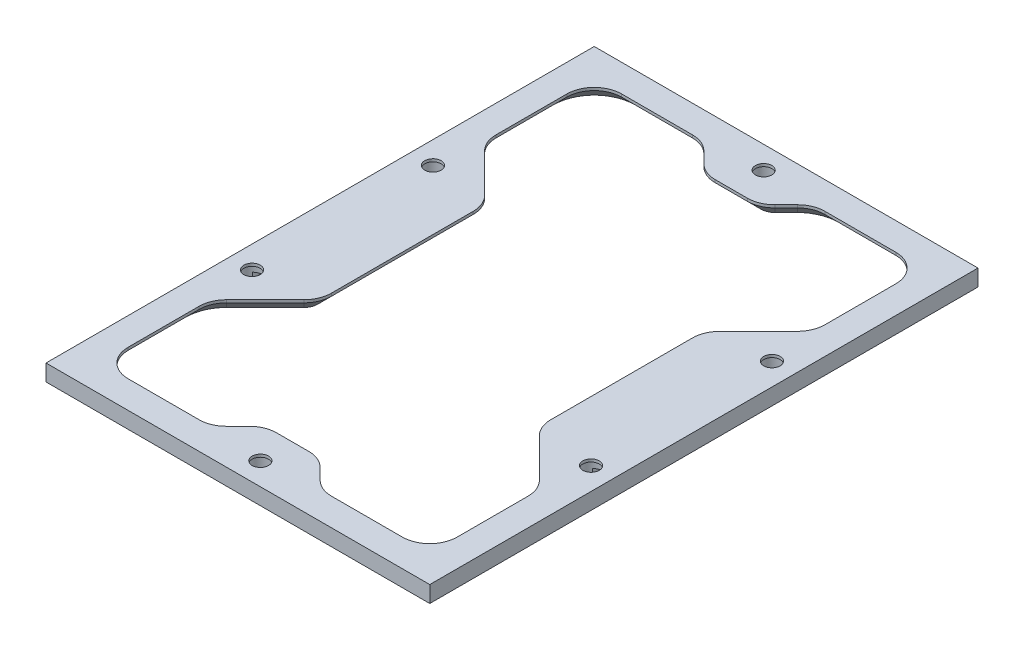
SolidWorks part; units mm, degrees
other "Markup1"
sketch "Sketch5" plane through (140, 0, -160) normal (0.8676, -0.3882, -0.3107) x (0.4165, 0.2261, 0.8806)
ref_plane "Front Plane" through (0, 0, 0) normal (0, 0, 1) x (1, 0, 0)
ref_plane "Top Plane" through (0, 0, 0) normal (0, 1, 0) x (1, 0, 0)
ref_plane "Right Plane" through (0, 0, 0) normal (1, 0, 0) x (0, 0, -1)
sketch "Sketch1" plane through (0, 0, 0) normal (0, 1, 0) x (1, 0, 0)
  line L0 (10, 190) -> (50, 190)
  line L1 (0, 0) -> (140, 0)
  line L2 (0, 0) -> (0, 200)
  line L3 (0, 200) -> (140, 200)
  line L4 (140, 0) -> (140, 200)
  line L5 (50, 190) -> (60, 180)
  line L6 (60, 180) -> (80, 180)
  line L7 (80, 180) -> (90, 190)
  line L8 (90, 190) -> (130, 190)
  line L9 (130, 190) -> (130, 150)
  line L10 (130, 150) -> (110, 130)
  line L11 (110, 130) -> (110, 70)
  line L12 (110, 70) -> (130, 50)
  line L13 (130, 50) -> (130, 10)
  line L14 (130, 10) -> (90, 10)
  line L15 (90, 10) -> (80, 20)
  line L16 (80, 20) -> (60, 20)
  line L17 (60, 20) -> (50, 10)
  line L18 (50, 10) -> (10, 10)
  line L19 (10, 10) -> (10, 50)
  line L20 (10, 50) -> (30, 70)
  line L21 (30, 70) -> (30, 130)
  line L22 (30, 130) -> (10, 150)
  line L23 (10, 150) -> (10, 190)
  dimension "D1" = 200
  dimension "D2" = 140
  dimension "D3" = 10
  dimension "D4" = 10
  dimension "D5" = 10
  dimension "D6" = 10
  dimension "D7" = 10
  dimension "D8" = 10
  dimension "D9" = 30
  dimension "D10" = 30
  dimension "D12" = 10
  dimension "D13" = 40
  dimension "D14" = 10
  dimension "D15" = 40
  dimension "D16" = 40
  dimension "D17" = 40
  dimension "D18" = 40
  dimension "D19" = 20
  dimension "D20" = 135
  dimension "D21" = 135
  dimension "D22" = 135
  dimension "D23" = 135
  dimension "D24" = 60
  dimension "D25" = 60
  dimension "D26" = 135
  dimension "D27" = 135
  dimension "D28" = 40
  dimension "D29" = 40
  dimension "D30" = 135
  dimension "D31" = 135
  dimension "D32" = 40
  dimension "D33" = 20
extrude "Boss-Extrude1" add sketch "Sketch1" along normal blind 6
fillet "Fillet1" radius 10 1 edges at (10, 3, -190)
fillet "Fillet2" radius 10 19 edges at (10, 3, -150) (30, 3, -130) (30, 3, -70) (10, 3, -50) (10, 3, -10) (50, 3, -10) (60, 3, -20) (80, 3, -20) (90, 3, -10) (130, 3, -10) (130, 3, -50) (110, 3, -70) (110, 3, -130) (130, 3, -150) (130, 3, -190) (90, 3, -190) (80, 3, -180) (60, 3, -180) (50, 3, -190)
chamfer "Chamfer4" distance 5 distance2 5 40 edges at (127.0711, 0, -187.0711) (107.0711, 0, -190) (90.3153, 0, -189.2388) (85, 0, -185) (79.6847, 0, -180.7612) (70, 0, -180) (60.3153, 0, -180.7612) (55, 0, -185) (49.6847, 0, -189.2388) (32.9289, 0, -190) (12.9289, 0, -187.0711) (10, 0, -167.0711) (10.7612, 0, -150.3153) (20, 0, -140) (29.2388, 0, -129.6847) (30, 0, -100) (29.2388, 0, -70.3153) (20, 0, -60) (10.7612, 0, -49.6847) (10, 0, -32.9289) (12.9289, 0, -12.9289) (32.9289, 0, -10) (49.6847, 0, -10.7612) (55, 0, -15) (60.3153, 0, -19.2388) (70, 0, -20) (79.6847, 0, -19.2388) (85, 0, -15) (90.3153, 0, -10.7612) (107.0711, 0, -10) (127.0711, 0, -12.9289) (130, 0, -32.9289) (129.2388, 0, -49.6847) (120, 0, -60) (110.7612, 0, -70.3153) (110, 0, -100) (110.7612, 0, -129.6847) (120, 0, -140) (129.2388, 0, -150.3153) (130, 0, -167.0711)
sketch "Sketch6" plane through (0, 0, 0) normal (0, -1, 0) x (1, 0, 0)
  line L0 (70, -200) -> (70, 0) construction
  line L1 (140, -200) -> (0, -200) construction
  line L2 (0, 0) -> (140, 0) construction
  line L3 (121, -125) -> (121, -75) construction
  line L4 (118, -125) -> (118, -75)
  line L5 (124, -125) -> (124, -75)
  line L6 (132, -133.0286) -> (132, -67.0286) construction
  line L7 (129, -133.0286) -> (129, -67.0286)
  line L8 (135, -133.0286) -> (135, -67.0286)
  line L9 (140, 0) -> (140, -200) construction
  line L11 (115, -74.1421) -> (115, -125.8579) construction
  line L12 (115, -100) -> (159.3934, -100) construction
  line L13 (19, -125) -> (19, -75) construction
  line L14 (22, -125) -> (22, -75)
  line L15 (16, -125) -> (16, -75)
  line L16 (8, -133.0286) -> (8, -67.0286) construction
  line L17 (11, -133.0286) -> (11, -67.0286)
  line L18 (5, -133.0286) -> (5, -67.0286)
  arc A0 (118, -125) -> (124, -125) centre (121, -125) ccw
  arc A1 (124, -75) -> (118, -75) centre (121, -75) ccw
  arc A2 (129, -133.0286) -> (135, -133.0286) centre (132, -133.0286) ccw
  arc A3 (135, -67.0286) -> (129, -67.0286) centre (132, -67.0286) ccw
  arc A4 (22, -125) -> (16, -125) centre (19, -125) cw
  arc A5 (16, -75) -> (22, -75) centre (19, -75) cw
  arc A6 (11, -133.0286) -> (5, -133.0286) centre (8, -133.0286) cw
  arc A7 (5, -67.0286) -> (11, -67.0286) centre (8, -67.0286) cw
  point P8 (121, -100)
  point P13 (132, -100.0286)
  point P30 (19, -100)
  point P37 (8, -100.0286)
  dimension "D1" = 3
  dimension "D2" = 3
  dimension "D3" = 5
  dimension "D4" = 5
  dimension "D5" = 0
  dimension "D6" = 33
  dimension "D7" = 25
extrude "Cut-Extrude1" cut sketch "Sketch6" against normal blind 2
sketch "Sketch7" plane through (0, 6, 0) normal (0, 1, 0) x (1, 0, 0)
  line L0 (0, 100) -> (140, 100) construction
  line L1 (0, 200) -> (0, 0) construction
  line L2 (140, 0) -> (140, 200) construction
  line L3 (70, 0) -> (70, 200) construction
  line L4 (0, 0) -> (140, 0) construction
  line L5 (140, 200) -> (0, 200) construction
  line L6 (140, 200) -> (0, 200) construction
  line L7 (0, 200) -> (0, 0) construction
  circle A0 centre (70, 191.8) radius 3
  circle A2 centre (8.1661, 133) radius 3
  circle A3 centre (70, 8.2) radius 3
  circle A4 centre (8.1661, 67) radius 3
  circle A5 centre (131.8339, 67) radius 3
  circle A6 centre (131.8339, 133) radius 3
  dimension "D1" = 6
  dimension "D3" = 8.1661
  dimension "D4" = 8.2
  dimension "D5" = 70
  dimension "D6" = 6
  dimension "D2" = 33
extrude "Cut-Extrude3" cut sketch "Sketch7" against normal blind 10
sketch "Sketch8" plane through (0, 0, 0) normal (0, -1, 0) x (1, 0, 0)
  line L0 (0, -100) -> (140, -100) construction
  line L1 (0, -200) -> (0, 0) construction
  line L2 (140, 0) -> (140, -200) construction
  line L3 (70, -200) -> (70, 0) construction
  line L4 (140, -200) -> (0, -200) construction
  line L5 (0, 0) -> (140, 0) construction
  circle A0 centre (70, -8.2) radius 4.5
  circle A1 centre (8, -67.0286) radius 4.5
  circle A2 centre (132, -67.0286) radius 4.5
  circle A3 centre (8, -132.9714) radius 4.5
  circle A4 centre (70, -191.8) radius 4.5
  circle A5 centre (132, -132.9714) radius 4.5
  dimension "D1" = 9
  dimension "D2" = 9
extrude "Cut-Extrude4" cut sketch "Sketch8" against normal blind 5
